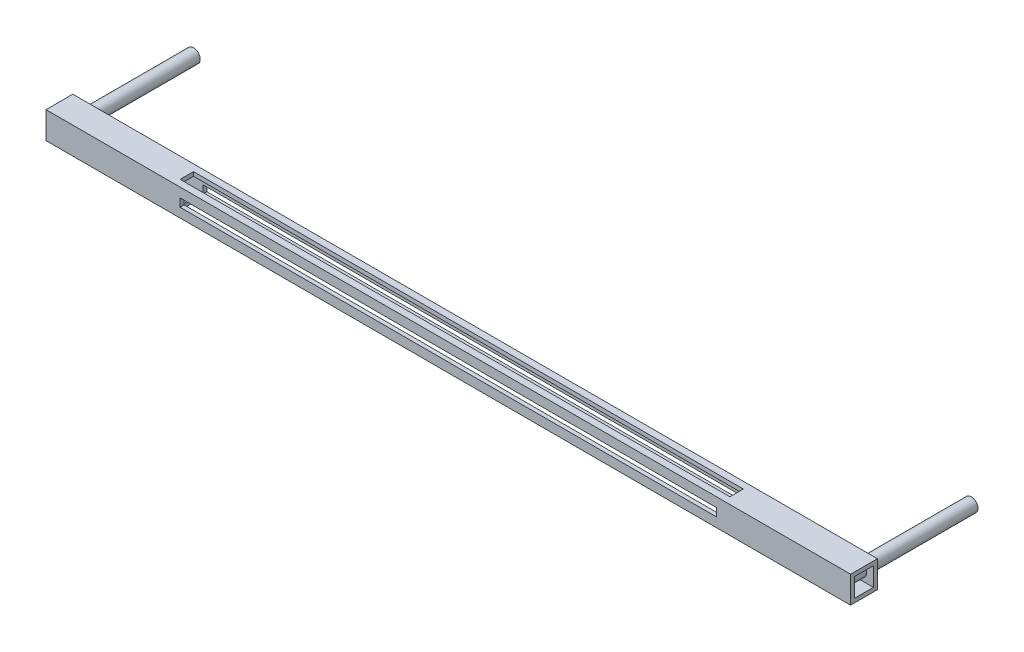
SolidWorks part; units mm, degrees
ref_plane "Front Plane" through (0, 0, 0) normal (1, 0, 0) x (0, 1, 0)
ref_plane "Top Plane" through (0, 0, 0) normal (0, 0, 1) x (0, 1, 0)
ref_plane "Right Plane" through (0, 0, 0) normal (0, 1, 0) x (-1, 0, 0)
sketch "Sketch13" plane through (0, 0, 0) normal (1, 0, 0) x (0, 1, 0)
  line L1 (5, 5) -> (-5, 5)
  line L2 (5, 5) -> (5, -5)
  line L3 (5, -5) -> (-5, -5)
  line L4 (-5, 5) -> (-5, -5)
  line L5 (3.5, 3.5) -> (-3.5, 3.5)
  line L6 (3.5, 3.5) -> (3.5, -3.5)
  line L7 (3.5, -3.5) -> (-3.5, -3.5)
  line L8 (-3.5, 3.5) -> (-3.5, -3.5)
  dimension "D1" = 7
  dimension "D2" = 10
  dimension "D3" = 10
extrude "Boss-Extrude1" add sketch "Sketch13" along normal blind 300
sketch "Sketch15" plane through (0, 5, 0) normal (0, 1, 0) x (-1, 0, 0)
  line L6 (-300, -5) -> (-300, 5) construction
  line L7 (-252.5, 2.5) -> (-47.5, 2.5)
  line L8 (-252.5, 2.5) -> (-252.5, -2.5)
  line L9 (-252.5, -2.5) -> (-47.5, -2.5)
  line L10 (-47.5, 2.5) -> (-47.5, -2.5)
  line L11 (-300, 5) -> (0, 5) construction
  dimension "D1" = 205
  dimension "D2" = 47.5
  dimension "D3" = 5
  dimension "D4" = 2.5
extrude "Cut-Extrude1" cut sketch "Sketch15" against normal blind 740
sketch "Sketch16" plane through (0, 0, 5) normal (0, 0, 1) x (1, 0, 0)
  line L0 (150, 5) -> (150, -17.3248) construction
  line L1 (300, 5) -> (0, 5) construction
  circle A0 centre (5, 0) radius 2.5
  circle A1 centre (295, 0) radius 2.5
  dimension "D1" = 5
  dimension "D2" = 5
  dimension "D3" = 5
extrude "Boss-Extrude3" add sketch "Sketch16" against normal blind 50
sketch "Sketch17" plane through (0, 0, 5) normal (0, 0, 1) x (1, 0, 0)
  line L0 (0, 5) -> (0, -5) construction
  line L1 (50, 1.5) -> (250, 1.5)
  line L2 (50, 1.5) -> (50, -1.5)
  line L3 (50, -1.5) -> (250, -1.5)
  line L4 (250, 1.5) -> (250, -1.5)
  line L5 (300, 5) -> (0, 5) construction
  dimension "D1" = 200
  dimension "D2" = 50
  dimension "D3" = 3
  dimension "D4" = 3.5
extrude "Cut-Extrude2" cut sketch "Sketch17" against normal blind 70
sketch "Sketch18" plane through (0, 0, -5) normal (0, 0, -1) x (-1, 0, 0)
  line L0 (0, 0) -> (-300, 0) construction
  line L1 (-300, -5) -> (-300, 5) construction
  line L2 (-150, -5) -> (-150, 5) construction
  line L3 (-300, -5) -> (0, -5) construction
  line L4 (-300, 5) -> (0, 5) construction
sketch "Sketch19" plane through (250, 0, 0) normal (-1, 0, 0) x (0, -1, 0)
  line L0 (0, -5) -> (0, 5) construction
  line L1 (5, -5) -> (-5, -5) construction
  line L2 (-5, 5) -> (5, 5) construction
